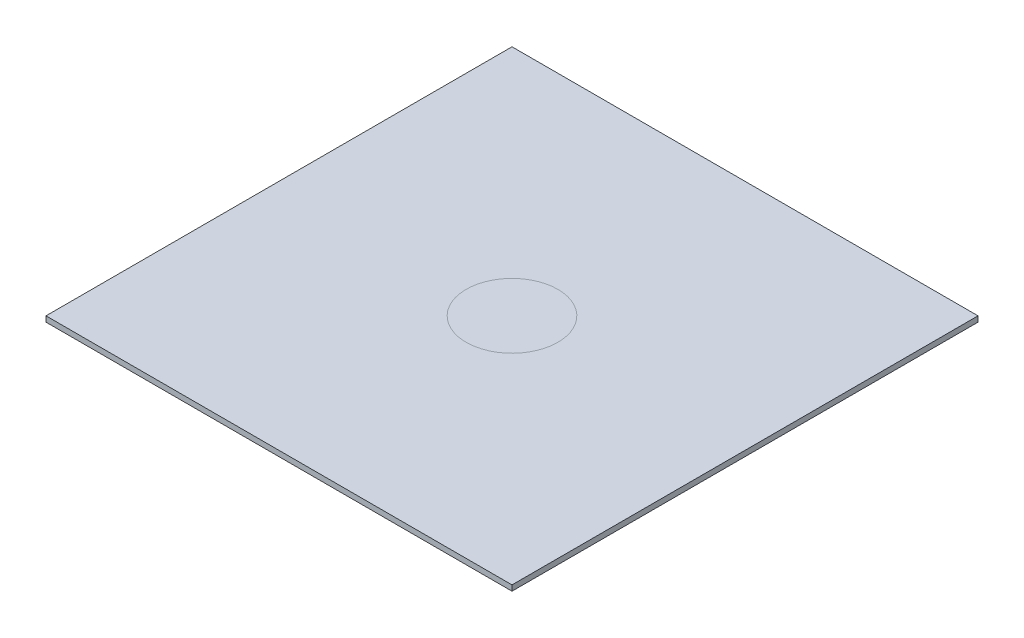
SolidWorks part; units mm, degrees
material "Polyetheretherketone (PEEK)"
ref_plane "Front Plane" through (0, 0, 0) normal (0, 0, 1) x (1, 0, 0)
ref_plane "Top Plane" through (0, 0, 0) normal (0, 1, 0) x (1, 0, 0)
ref_plane "Right Plane" through (0, 0, 0) normal (1, 0, 0) x (0, 0, -1)
sketch "Sketch1" plane through (0, 0, 0) normal (0, 1, 0) x (1, 0, 0)
  line L1 (-127, -127) -> (127, -127)
  line L2 (-127, -127) -> (-127, 127)
  line L3 (-127, 127) -> (127, 127)
  line L4 (127, -127) -> (127, 127)
  line L5 (-127, -127) -> (127, 127) construction
  line L6 (-127, 127) -> (127, -127) construction
  point P0 (0, 0)
  dimension "D1" = 254
extrude "Boss-Extrude1" add sketch "Sketch1" along normal mid plane 3
sketch "Sketch3" plane through (0, -1.5, 0) normal (0, -1, 0) x (1, 0, 0)
  line L0 (127, 127) -> (127, -127) construction
  line L1 (-107, -107) -> (107, -107)
  line L2 (-107, -107) -> (-107, 107)
  line L3 (-107, 107) -> (107, 107)
  line L4 (107, -107) -> (107, 107)
  line L5 (-107, -107) -> (107, 107) construction
  line L6 (-107, 107) -> (107, -107) construction
  point P0 (0, 0)
  dimension "D1" = 20
split line "Split Line1"
sketch "Sketch4" plane through (0, 1.5, 0) normal (0, 1, 0) x (1, 0, 0)
  circle A0 centre (0, 0) radius 25
  dimension "D1" = 50
split line "Split Line2"
